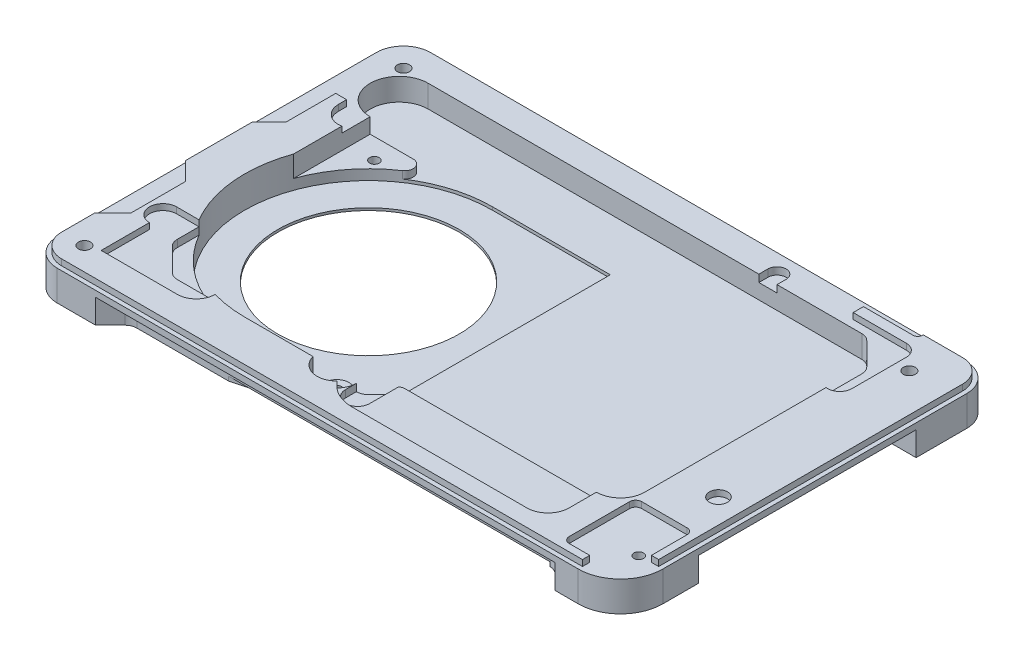
SolidWorks part; units mm, degrees
ref_plane "Front Plane" through (0, 0, 0) normal (0, 0, 1) x (1, 0, 0)
ref_plane "Top Plane" through (0, 0, 0) normal (0, 1, 0) x (1, 0, 0)
ref_plane "Right Plane" through (0, 0, 0) normal (1, 0, 0) x (0, 0, -1)
sketch "Sketch5" plane through (0, 0, 0) normal (0, 1, 0) x (1, 0, 0)
  line L1 (-44.35, -30.89) -> (41.85, -30.89)
  line L2 (-48.85, -26.39) -> (-48.85, 26.39)
  line L3 (-44.35, 30.89) -> (44.35, 30.89)
  line L4 (48.85, -23.89) -> (48.85, 26.39)
  line L5 (-48.85, -30.89) -> (48.85, 30.89) construction
  line L6 (-48.85, 30.89) -> (48.85, -30.89) construction
  arc A0 (48.85, 26.39) -> (44.35, 30.89) centre (44.35, 26.39) ccw
  arc A1 (-44.35, 30.89) -> (-48.85, 26.39) centre (-44.35, 26.39) ccw
  arc A2 (-48.85, -26.39) -> (-44.35, -30.89) centre (-44.35, -26.39) ccw
  arc A3 (41.85, -30.89) -> (48.85, -23.89) centre (41.85, -23.89) ccw
  point P0 (0, 0)
  point P18 (48.85, -22.4538)
  dimension "D3" = 4.5
  dimension "D4" = 7
  dimension "D1" = 97.7
  dimension "D2" = 61.78
extrude "Boss-Extrude2" add sketch "Sketch5" along normal blind 5
sketch "Sketch6" plane through (0, 0, 0) normal (0, -1, 0) x (1, 0, 0)
  line L0 (0, 30.89) -> (0, -30.89) construction
  line L2 (44.35, -30.89) -> (-44.35, -30.89) construction
  line L3 (-48.85, 0) -> (48.85, 0) construction
  line L4 (-48.85, -26.39) -> (-48.85, 26.39) construction
  line L6 (-47.95, 26.39) -> (-47.95, 20.2366)
  line L7 (-46.7331, 19.2604) -> (-39.7331, 20.816)
  line L8 (-38.95, 21.7922) -> (-38.95, 28.99)
  line L9 (-39.95, 29.99) -> (-44.35, 29.99)
  line L10 (39.95, 29.99) -> (41.85, 29.99)
  line L11 (38.95, 21.7922) -> (38.95, 28.99)
  line L12 (46.7331, 19.2604) -> (39.7331, 20.816)
  line L13 (47.95, 23.89) -> (47.95, 20.2366)
  line L14 (48.7658, -22.89) -> (47.95, -20.2366)
  line L15 (46.7331, -19.2604) -> (39.7331, -20.816)
  line L16 (38.95, -21.7922) -> (38.95, -28.99)
  line L17 (39.95, -29.99) -> (44.4999, -30.3558)
  line L18 (-39.95, -29.99) -> (-44.35, -29.99)
  line L19 (-38.95, -21.7922) -> (-38.95, -28.99)
  line L20 (-46.7331, -19.2604) -> (-39.7331, -20.816)
  line L21 (-47.95, -26.39) -> (-47.95, -20.2366)
  arc A0 (-47.95, 26.39) -> (-44.35, 29.99) centre (-44.35, 26.39) cw
  arc A1 (-44.35, 30.89) -> (-48.85, 26.39) centre (-44.35, 26.39) ccw construction
  arc A2 (-38.95, 21.7922) -> (-39.7331, 20.816) centre (-39.95, 21.7922) cw
  arc A3 (-39.95, 29.99) -> (-38.95, 28.99) centre (-39.95, 28.99) cw
  arc A4 (-47.95, 20.2366) -> (-46.7331, 19.2604) centre (-46.95, 20.2366) ccw
  arc A5 (47.95, 20.2366) -> (46.7331, 19.2604) centre (46.95, 20.2366) cw
  arc A6 (39.95, 29.99) -> (38.95, 28.99) centre (39.95, 28.99) ccw
  arc A7 (38.95, 21.7922) -> (39.7331, 20.816) centre (39.95, 21.7922) ccw
  arc A8 (47.95, 23.89) -> (41.85, 29.99) centre (41.85, 23.89) ccw
  arc A9 (48.7658, -22.89) -> (44.4999, -30.3558) centre (41.85, -23.89) cw
  arc A10 (38.95, -21.7922) -> (39.7331, -20.816) centre (39.95, -21.7922) cw
  arc A11 (39.95, -29.99) -> (38.95, -28.99) centre (39.95, -28.99) cw
  arc A12 (47.95, -20.2366) -> (46.7331, -19.2604) centre (46.95, -20.2366) ccw
  arc A13 (-47.95, -20.2366) -> (-46.7331, -19.2604) centre (-46.95, -20.2366) cw
  arc A14 (-39.95, -29.99) -> (-38.95, -28.99) centre (-39.95, -28.99) ccw
  arc A15 (-38.95, -21.7922) -> (-39.7331, -20.816) centre (-39.95, -21.7922) ccw
  arc A16 (-47.95, -26.39) -> (-44.35, -29.99) centre (-44.35, -26.39) ccw
  arc A17 (48.85, 23.89) -> (41.85, 30.89) centre (41.85, 23.89) ccw construction
  point P3 (0, 0)
  point P10 (0, 0)
  point P25 (-38.95, 20.99)
  point P28 (-38.95, 29.99)
  point P31 (-47.95, 18.99)
  dimension "D1" = 3.6
  dimension "D2" = 0.9
  dimension "D6" = 1
  dimension "D3" = 9
  dimension "D4" = 9
  dimension "D5" = 11
sketch "Sketch10" plane through (0, 0, 0) normal (0, -1, 0) x (1, 0, 0)
  line L0 (-48.85, 18) -> (-44.4358, 13.5858)
  line L1 (-48.85, -26.39) -> (-48.85, 26.39) construction
  line L2 (-43.85, 12.1716) -> (-43.85, -12.1716)
  line L3 (-44.4358, -13.5858) -> (-48.85, -18)
  line L4 (-48.85, -18) -> (-48.85, 18)
  line L5 (-48.85, 0) -> (48.85, 0) construction
  line L6 (48.85, 23.89) -> (48.85, -26.39) construction
  line L7 (0, 30.89) -> (0, -30.89) construction
  line L9 (44.35, -30.89) -> (-44.35, -30.89) construction
  line L10 (-38, -30.89) -> (-35.5858, -28.4758)
  line L11 (-34.1716, -27.89) -> (34.1716, -27.89)
  line L12 (35.5858, -28.4758) -> (38, -30.89)
  line L13 (-38, -30.89) -> (38, -30.89)
  line L14 (-38, 30.89) -> (38, 30.89)
  line L15 (35.5858, 28.4758) -> (38, 30.89)
  line L16 (-34.1716, 27.89) -> (34.1716, 27.89)
  line L17 (-38, 30.89) -> (-35.5858, 28.4758)
  line L21 (36.85, 18) -> (48.85, 18)
  line L22 (48.85, -18) -> (48.85, 18)
  line L23 (36.85, 15.2) -> (44.85, 15.2)
  line L24 (44.85, 15.2) -> (44.85, 14.1)
  line L25 (44.85, 14.1) -> (36.85, 14.1)
  line L27 (36.85, 11.9444) -> (44.85, 11.9444)
  line L28 (44.85, 11.9444) -> (44.85, 10.8444)
  line L29 (44.85, 10.8444) -> (36.85, 10.8444)
  line L30 (36.85, 8.6889) -> (44.85, 8.6889)
  line L31 (44.85, 8.6889) -> (44.85, 7.5889)
  line L32 (44.85, 7.5889) -> (36.85, 7.5889)
  line L33 (36.85, 5.4333) -> (44.85, 5.4333)
  line L34 (44.85, 5.4333) -> (44.85, 4.3333)
  line L35 (44.85, 4.3333) -> (36.85, 4.3333)
  line L36 (36.85, 2.1778) -> (44.85, 2.1778)
  line L37 (44.85, 2.1778) -> (44.85, 1.0778)
  line L38 (44.85, 1.0778) -> (36.85, 1.0778)
  line L41 (36.85, -1.0778) -> (44.85, -1.0778) [skipped]
  line L42 (44.85, -1.0778) -> (44.85, -2.1778) [skipped]
  line L43 (44.85, -1.0778) -> (36.85, -1.0778)
  line L44 (44.85, -2.1778) -> (44.85, -1.0778)
  line L45 (36.85, -2.1778) -> (44.85, -2.1778)
  line L46 (44.85, -4.3333) -> (36.85, -4.3333)
  line L47 (44.85, -5.4333) -> (44.85, -4.3333)
  line L48 (36.85, -5.4333) -> (44.85, -5.4333)
  line L49 (44.85, -7.5889) -> (36.85, -7.5889)
  line L50 (44.85, -8.6889) -> (44.85, -7.5889)
  line L51 (36.85, -8.6889) -> (44.85, -8.6889)
  line L52 (44.85, -10.8444) -> (36.85, -10.8444)
  line L53 (44.85, -11.9444) -> (44.85, -10.8444)
  line L54 (36.85, -11.9444) -> (44.85, -11.9444)
  line L55 (44.85, -14.1) -> (36.85, -14.1)
  line L56 (44.85, -15.2) -> (44.85, -14.1)
  line L57 (36.85, -15.2) -> (44.85, -15.2)
  line L59 (36.85, -18) -> (48.85, -18)
  arc A0 (-43.85, -12.1716) -> (-44.4358, -13.5858) centre (-45.85, -12.1716) cw
  arc A1 (-44.4358, 13.5858) -> (-43.85, 12.1716) centre (-45.85, 12.1716) cw
  arc A2 (35.5858, -28.4758) -> (34.1716, -27.89) centre (34.1716, -29.89) ccw
  arc A3 (-34.1716, -27.89) -> (-35.5858, -28.4758) centre (-34.1716, -29.89) ccw
  arc A4 (-34.1716, 27.89) -> (-35.5858, 28.4758) centre (-34.1716, 29.89) cw
  arc A5 (35.5858, 28.4758) -> (34.1716, 27.89) centre (34.1716, 29.89) cw
  arc A6 (36.85, 14.1) -> (36.85, 11.9444) centre (36.85, 13.0222) ccw
  arc A7 (36.85, 18) -> (36.85, 15.2) centre (36.85, 16.6) ccw
  arc A8 (36.85, 10.8444) -> (36.85, 8.6889) centre (36.85, 9.7667) ccw
  arc A9 (36.85, 7.5889) -> (36.85, 5.4333) centre (36.85, 6.5111) ccw
  arc A10 (36.85, 4.3333) -> (36.85, 2.1778) centre (36.85, 3.2556) ccw
  arc A11 (36.85, 1.0778) -> (36.85, -1.0778) centre (36.85, 0) ccw
  arc A12 (36.85, -4.3333) -> (36.85, -2.1778) centre (36.85, -3.2556) cw
  arc A13 (36.85, -7.5889) -> (36.85, -5.4333) centre (36.85, -6.5111) cw
  arc A14 (36.85, -10.8444) -> (36.85, -8.6889) centre (36.85, -9.7667) cw
  arc A15 (36.85, -18) -> (36.85, -15.2) centre (36.85, -16.6) cw
  arc A16 (36.85, -14.1) -> (36.85, -11.9444) centre (36.85, -13.0222) cw
  dimension "D4" = 2
  dimension "D8" = 2
  dimension "D15" = 36
  dimension "D1" = 5
  dimension "D2" = 135
  dimension "D3" = 36
  dimension "D5" = 76
  dimension "D6" = 135
  dimension "D7" = 3
  dimension "D9" = 5
  dimension "D10" = 8
  dimension "D11" = 1.1
  dimension "D12" = 12
  dimension "D13" = 8
  dimension "D14" = 2.8
extrude "Cut-Extrude2" cut sketch "Sketch10" against normal blind 4
sketch "Sketch11" plane through (0, 4, 0) normal (0, -1, 0) x (1, 0, 0)
  line L0 (-35.5858, -28.4758) -> (-38, -30.89) construction
  line L1 (-38, 30.89) -> (-35.5858, 28.4758) construction
  line L2 (-34.1716, 27.89) -> (34.1716, 27.89) construction
  line L3 (35.5858, 28.4758) -> (38, 30.89) construction
  line L4 (38, -30.89) -> (35.5858, -28.4758) construction
  line L5 (34.1716, -27.89) -> (-34.1716, -27.89) construction
  line L6 (-35.5858, -28.4758) -> (-36.5, -29.39)
  line L7 (-36.5, 29.39) -> (-35.5858, 28.4758)
  line L8 (-34.1716, 27.89) -> (34.1716, 27.89)
  line L9 (35.5858, 28.4758) -> (36.5, 29.39)
  line L10 (36.5, -29.39) -> (35.5858, -28.4758)
  line L11 (34.1716, -27.89) -> (-34.1716, -27.89)
  line L12 (-36.5, -29.39) -> (36.5, -29.39)
  line L13 (-36.5, 29.39) -> (36.5, 29.39)
  line L14 (0, -27.89) -> (0, -29.39) construction
  line L15 (0, 29.39) -> (0, 27.89) construction
  arc A0 (-34.1716, -27.89) -> (-35.5858, -28.4758) centre (-34.1716, -29.89) ccw construction
  arc A1 (34.1716, 27.89) -> (35.5858, 28.4758) centre (34.1716, 29.89) ccw construction
  arc A2 (-35.5858, 28.4758) -> (-34.1716, 27.89) centre (-34.1716, 29.89) ccw construction
  arc A3 (35.5858, -28.4758) -> (34.1716, -27.89) centre (34.1716, -29.89) ccw construction
  arc A4 (-34.1716, -27.89) -> (-35.5858, -28.4758) centre (-34.1716, -29.89) ccw
  arc A5 (34.1716, 27.89) -> (35.5858, 28.4758) centre (34.1716, 29.89) ccw
  arc A6 (-35.5858, 28.4758) -> (-34.1716, 27.89) centre (-34.1716, 29.89) ccw
  arc A7 (35.5858, -28.4758) -> (34.1716, -27.89) centre (34.1716, -29.89) ccw
  dimension "D1" = 1.5
extrude "Boss-Extrude4" add sketch "Sketch11" along normal blind 1.2
sketch "Sketch12" plane through (0, 0, -15.2) normal (0, 0, -1) x (-1, 0, 0)
  line L1 (-44.85, 4) -> (-36.85, 0)
  line L6 (-44.85, 0) -> (-36.85, 0)
  line L12 (-36.85, 0) -> (-36.85, 4)
  line L13 (-36.85, 4) -> (-44.85, 4)
  line L14 (-44.85, 4) -> (-44.85, 0)
  line L15 (-44.85, 0) -> (-36.85, 0)
  line L16 (-36.85, 0) -> (-36.85, 4) construction
  line L17 (-36.85, 4) -> (-44.85, 4) construction
  line L18 (-44.85, 4) -> (-44.85, 0)
  dimension "D1" = 0
extrude "Cut-Extrude4" cut sketch "Sketch12" against normal up to surface (30.4 mm away) up to face at (40.85, 2, 15.2)
extrude "Cut-Extrude5" cut sketch "Sketch6" against normal blind 1
sketch "Sketch13" plane through (0, 1, 0) normal (0, -1, 0) x (1, 0, 0)
  line L0 (41.85, 29.99) -> (39.95, 29.99) construction
  line L1 (38.95, 28.99) -> (38.95, 21.7922) construction
  circle A0 centre (-44.35, 26.39) radius 1
  circle A1 centre (-44.35, -26.39) radius 1
  circle A2 centre (41.85, -23.89) radius 1
  circle A4 centre (44.95, 23.99) radius 0.8
  dimension "D1" = 2
  dimension "D2" = 6
  dimension "D4" = 1.6
  dimension "D3" = 6
extrude "Cut-Extrude6" cut sketch "Sketch13" against normal through all
sketch "Sketch14" plane through (48.85, 0, 0) normal (1, 0, 0) x (0, 0, -1)
  line L1 (18, 0) -> (18, 4) construction
  line L2 (15.2, 4) -> (18, 4) construction
  line L3 (15.2, 4) -> (15.2, 0) construction
  line L5 (-15.2, 0) -> (-15.2, 4) construction
  line L6 (-18, 4) -> (-15.2, 4) construction
  line L7 (-18, 4) -> (-18, 0) construction
  line L9 (14.1, 0) -> (14.1, 4) construction
  line L10 (11.9444, 4) -> (14.1, 4) construction
  line L11 (11.9444, 4) -> (11.9444, 0) construction
  line L13 (10.8444, 0) -> (10.8444, 4) construction
  line L14 (8.6889, 4) -> (10.8444, 4) construction
  line L15 (8.6889, 4) -> (8.6889, 0) construction
  line L17 (7.5889, 0) -> (7.5889, 4) construction
  line L18 (5.4333, 4) -> (7.5889, 4) construction
  line L19 (5.4333, 4) -> (5.4333, 0) construction
  line L21 (4.3333, 0) -> (4.3333, 4) construction
  line L22 (2.1778, 4) -> (4.3333, 4) construction
  line L23 (2.1778, 4) -> (2.1778, 0) construction
  line L25 (1.0778, 0) -> (1.0778, 4) construction
  line L26 (-1.0778, 4) -> (1.0778, 4) construction
  line L27 (-1.0778, 4) -> (-1.0778, 0) construction
  line L29 (-2.1778, 0) -> (-2.1778, 4) construction
  line L30 (-4.3333, 4) -> (-2.1778, 4) construction
  line L31 (-4.3333, 4) -> (-4.3333, 0) construction
  line L33 (-5.4333, 0) -> (-5.4333, 4) construction
  line L34 (-7.5889, 4) -> (-5.4333, 4) construction
  line L35 (-7.5889, 4) -> (-7.5889, 0) construction
  line L37 (-8.6889, 0) -> (-8.6889, 4) construction
  line L38 (-10.8444, 4) -> (-8.6889, 4) construction
  line L39 (-10.8444, 4) -> (-10.8444, 0) construction
  line L41 (-11.9444, 0) -> (-11.9444, 4) construction
  line L42 (-14.1, 4) -> (-11.9444, 4) construction
  line L43 (-14.1, 4) -> (-14.1, 0) construction
  line L45 (18, 0.6) -> (18, 4)
  line L46 (15.2, 4) -> (18, 4)
  line L47 (15.2, 4) -> (15.2, 0.6)
  line L49 (-15.2, 0.6) -> (-15.2, 4)
  line L50 (-18, 4) -> (-15.2, 4)
  line L51 (-18, 4) -> (-18, 0.6)
  line L53 (14.1, 0.6) -> (14.1, 4)
  line L54 (11.9444, 4) -> (14.1, 4)
  line L55 (11.9444, 4) -> (11.9444, 0.6)
  line L57 (10.8444, 0.6) -> (10.8444, 4)
  line L58 (8.6889, 4) -> (10.8444, 4)
  line L59 (8.6889, 4) -> (8.6889, 0.6)
  line L61 (7.5889, 0.6) -> (7.5889, 4)
  line L62 (5.4333, 4) -> (7.5889, 4)
  line L63 (5.4333, 4) -> (5.4333, 0.6)
  line L65 (4.3333, 0.6) -> (4.3333, 4)
  line L66 (2.1778, 4) -> (4.3333, 4)
  line L67 (2.1778, 4) -> (2.1778, 0.6)
  line L69 (1.0778, 0.6) -> (1.0778, 4)
  line L70 (-1.0778, 4) -> (1.0778, 4)
  line L71 (-1.0778, 4) -> (-1.0778, 0.6)
  line L73 (-2.1778, 0.6) -> (-2.1778, 4)
  line L74 (-4.3333, 4) -> (-2.1778, 4)
  line L75 (-4.3333, 4) -> (-4.3333, 0.6)
  line L77 (-5.4333, 0.6) -> (-5.4333, 4)
  line L78 (-7.5889, 4) -> (-5.4333, 4)
  line L79 (-7.5889, 4) -> (-7.5889, 0.6)
  line L81 (-8.6889, 0.6) -> (-8.6889, 4)
  line L82 (-10.8444, 4) -> (-8.6889, 4)
  line L83 (-10.8444, 4) -> (-10.8444, 0.6)
  line L85 (-11.9444, 0.6) -> (-11.9444, 4)
  line L86 (-14.1, 4) -> (-11.9444, 4)
  line L87 (-14.1, 4) -> (-14.1, 0.6)
  line L88 (-18, 0.6) -> (-15.2, 0.6)
  line L89 (-18, 0) -> (-15.2, 0) construction
  line L90 (-14.1, 0.6) -> (-11.9444, 0.6)
  line L91 (-10.8444, 0.6) -> (-8.6889, 0.6)
  line L92 (-7.5889, 0.6) -> (-5.4333, 0.6)
  line L93 (-4.3333, 0.6) -> (-2.1778, 0.6)
  line L94 (-1.0778, 0.6) -> (1.0778, 0.6)
  line L95 (2.1778, 0.6) -> (4.3333, 0.6)
  line L96 (5.4333, 0.6) -> (7.5889, 0.6)
  line L97 (8.6889, 0.6) -> (10.8444, 0.6)
  line L98 (11.9444, 0.6) -> (14.1, 0.6)
  line L99 (15.2, 0.6) -> (18, 0.6)
  dimension "D1" = 0.6
sketch "Sketch15" plane through (0, 0, 0) normal (0, -1, 0) x (1, 0, 0)
  line L0 (-19, 27.89) -> (22.5938, 16.89)
  line L1 (24.5193, 17.4093) -> (35, 27.89)
  line L2 (-34.1716, 27.89) -> (34.1716, 27.89) construction
  line L3 (-48.85, 0) -> (48.85, 0) construction
  line L4 (-48.85, 18) -> (-48.85, -18) construction
  line L5 (48.85, -18) -> (48.85, 18) construction
  line L6 (35, 27.89) -> (-19, 27.89)
  line L7 (35, -27.89) -> (-19, -27.89)
  line L8 (24.5193, -17.4093) -> (35, -27.89)
  line L9 (-19, -27.89) -> (22.5938, -16.89)
  line L10 (38, -30.89) -> (35.5858, -28.4758) construction
  arc A0 (22.5938, -16.89) -> (24.5193, -17.4093) centre (23.1051, -18.8235) cw
  arc A1 (24.5193, 17.4093) -> (22.5938, 16.89) centre (23.1051, 18.8235) cw
  point P20 (23.7059, -16.5959)
  point P23 (23.7059, 16.5959)
  dimension "D3" = 2
  dimension "D1" = 54
  dimension "D2" = 11
extrude "Cut-Extrude8" cut sketch "Sketch15" against normal blind 0.7
sketch "Sketch16" plane through (0, 5, 0) normal (0, 1, 0) x (1, 0, 0)
  line L0 (-40.15, 26.29) -> (31.5718, 26.29)
  line L1 (32.986, 25.7042) -> (36.7642, 21.926)
  line L2 (37.35, 20.5118) -> (37.35, -15.39)
  line L3 (33.35, -19.39) -> (1.8069, -19.39)
  line L4 (0.3926, -19.9758) -> (-1.6858, -22.0542)
  line L7 (-34.186, -22.0042) -> (-37.9642, -18.226)
  line L8 (-38.55, -16.8118) -> (-38.55, -13.2321)
  line L9 (-40.15, 4.0209) -> (-40.15, 16.69)
  line L10 (44.35, 30.89) -> (-44.35, 30.89) construction
  line L11 (-48.85, 26.39) -> (-48.85, -26.39) construction
  line L12 (48.85, -23.89) -> (48.85, 26.39) construction
  line L13 (-44.35, -30.89) -> (41.85, -30.89) construction
  line L14 (-32.7718, -22.59) -> (-26.521, -22.59)
  line L15 (-9.5123, -23.39) -> (-20.85, -23.39)
  line L16 (-3.1, -22.64) -> (-9.5123, -22.64) construction
  arc A0 (-9.5123, -23.39) -> (-3.1, -22.64) centre (-6.35, -22.64) ccw
  arc A2 (-40.15, 26.29) -> (-40.15, 16.69) centre (-40.15, 21.49) ccw
  arc A3 (-40.15, 4.0209) -> (-38.55, -13.2321) centre (-20.85, -2.89) ccw
  circle A4 centre (-20.85, -2.89) radius 20.5 construction
  arc A5 (-26.521, -22.59) -> (-20.85, -23.39) centre (-20.85, -2.89) ccw
  arc A6 (37.35, -15.39) -> (33.35, -19.39) centre (33.35, -15.39) cw
  arc A7 (0.3926, -19.9758) -> (1.8069, -19.39) centre (1.8069, -21.39) cw
  arc A8 (-1.6858, -22.0542) -> (-3.1, -22.64) centre (-3.1, -20.64) cw
  arc A9 (-37.9642, -18.226) -> (-38.55, -16.8118) centre (-36.55, -16.8118) cw
  arc A10 (-34.186, -22.0042) -> (-32.7718, -22.59) centre (-32.7718, -20.59) ccw
  arc A11 (32.986, 25.7042) -> (31.5718, 26.29) centre (31.5718, 24.29) ccw
  arc A12 (36.7642, 21.926) -> (37.35, 20.5118) centre (35.35, 20.5118) cw
  point P26 (0, 0)
  point P27 (0, 0)
  point P31 (-6.35, -25.89)
  point P39 (1.2405, -22.64)
  point P45 (-33.6003, -22.59)
  point P48 (32.4003, 26.29)
  point P51 (37.35, 21.3403)
  dimension "D1" = 9.6
  dimension "D3" = 8.7
  dimension "D8" = 0.75
  dimension "D9" = 3.25
  dimension "D10" = 20.5
  dimension "D13" = 28
  dimension "D19" = 4
  dimension "D20" = 2
  dimension "D21" = 2
  dimension "D22" = 3.25
  dimension "D2" = 4.6
  dimension "D4" = 11.5
  dimension "D5" = 135
  dimension "D6" = 7
  dimension "D7" = 11.5
  dimension "D11" = 7.5
  dimension "D12" = 10.3
  dimension "D15" = 5
  dimension "D16" = 42.5
  dimension "D17" = 7.0793
  dimension "D18" = 8.3
extrude "Cut-Extrude10" cut sketch "Sketch16" against normal blind 3.7
sketch "Sketch17" plane through (0, 5, 0) normal (0, 1, 0) x (1, 0, 0)
  line L0 (-48.15, -20.89) -> (-48.15, -26.39)
  line L1 (-48.85, 26.39) -> (-48.85, -26.39) construction
  line L2 (-44.35, -30.89) -> (41.85, -30.89) construction
  line L3 (37.85, 30.19) -> (37.85, 30.09)
  line L4 (-48.15, 5.19) -> (-45.35, 7.99)
  line L5 (-45.35, 7.99) -> (-45.35, 16.19)
  line L6 (-45.35, 16.19) -> (-43.55, 16.19)
  line L7 (-43.55, 16.19) -> (-43.55, 14.8466)
  line L8 (-44.35, -30.19) -> (41.85, -30.19)
  line L9 (48.15, -23.89) -> (48.15, 26.39)
  line L10 (44.35, 30.19) -> (-44.35, 30.19)
  line L11 (-48.15, 26.39) -> (-48.15, -26.39)
  line L12 (-44.35, -30.19) -> (41.85, -30.19)
  line L13 (48.15, -23.89) -> (48.15, 26.39)
  line L14 (44.35, 30.19) -> (37.85, 30.19)
  line L15 (-48.15, 5.19) -> (-48.15, -5.89)
  line L16 (-42.25, -17.7321) -> (-42.25, -25.7154)
  line L17 (-40.15, 16.69) -> (-40.15, 4.0209) construction
  line L18 (-40.15, 16.69) -> (-40.15, 4.0209)
  line L19 (-20.85, -23.39) -> (-9.5123, -23.39) construction
  line L20 (-20.85, -23.39) -> (-9.5123, -23.39)
  line L21 (37.35, -15.39) -> (37.35, 20.5118) construction
  line L22 (37.35, -15.39) -> (37.35, 14.59)
  line L23 (-48.15, -5.89) -> (-45.15, -8.89)
  line L24 (-45.15, -8.89) -> (-45.15, -17.89)
  line L25 (-45.15, -17.89) -> (-48.15, -20.89)
  line L26 (-38.55, -13.2321) -> (-42.25, -13.2321)
  line L27 (-42.25, -25.7154) -> (-29.6464, -25.7154)
  line L28 (-32.7718, -22.59) -> (-26.521, -22.59) construction
  line L29 (37.05, 29.29) -> (28.85, 29.29)
  line L30 (28.85, 29.29) -> (28.85, 27.59)
  line L31 (28.85, 27.59) -> (37.65, 27.59)
  line L32 (39.65, 25.59) -> (39.65, 16.59)
  line L33 (37.65, 14.59) -> (37.35, 14.59)
  line L34 (-4.0519, -24.9381) -> (-3.3574, -25.6326)
  line L35 (0.8853, -27.39) -> (29.85, -27.39)
  line L36 (33.35, -23.89) -> (33.35, -19.39)
  line L37 (41.85, -28.99) -> (41.85, -30.19)
  line L38 (38.45, -28.99) -> (41.85, -28.99)
  line L39 (37.45, -27.99) -> (37.45, -17.99)
  line L40 (38.45, -16.99) -> (45.95, -16.99)
  line L41 (46.95, -23.89) -> (46.95, -17.99)
  line L42 (46.95, -23.89) -> (48.15, -23.89)
  line L44 (44.35, 30.89) -> (-44.35, 30.89) construction
  line L45 (48.85, -23.89) -> (48.85, 26.39) construction
  arc A0 (-9.5123, -23.39) -> (-3.1, -22.64) centre (-6.35, -22.64) ccw construction
  arc A1 (-9.5123, -23.39) -> (-4.0519, -24.9381) centre (-6.35, -22.64) ccw
  arc A2 (37.45, -27.99) -> (38.45, -28.99) centre (38.45, -27.99) ccw
  arc A3 (45.95, -16.99) -> (46.95, -17.99) centre (45.95, -17.99) cw
  arc A4 (-40.15, 4.0209) -> (-38.55, -13.2321) centre (-20.85, -2.89) ccw construction
  arc A5 (-40.15, 4.0209) -> (-38.55, -13.2321) centre (-20.85, -2.89) ccw
  arc A6 (-26.521, -22.59) -> (-20.85, -23.39) centre (-20.85, -2.89) ccw construction
  arc A7 (-26.521, -22.59) -> (-20.85, -23.39) centre (-20.85, -2.89) ccw
  arc A8 (-48.15, -26.39) -> (-44.35, -30.19) centre (-44.35, -26.39) ccw
  arc A9 (41.85, -30.19) -> (48.15, -23.89) centre (41.85, -23.89) ccw
  arc A10 (48.15, 26.39) -> (44.35, 30.19) centre (44.35, 26.39) ccw
  arc A11 (-44.35, 30.19) -> (-48.15, 26.39) centre (-44.35, 26.39) ccw
  arc A12 (-48.15, -26.39) -> (-44.35, -30.19) centre (-44.35, -26.39) ccw
  arc A13 (41.85, -30.19) -> (48.15, -23.89) centre (41.85, -23.89) ccw
  arc A14 (48.15, 26.39) -> (44.35, 30.19) centre (44.35, 26.39) ccw
  arc A16 (33.35, -19.39) -> (37.35, -15.39) centre (33.35, -15.39) ccw construction
  arc A17 (33.35, -19.39) -> (37.35, -15.39) centre (33.35, -15.39) ccw
  arc A18 (-43.55, 14.8466) -> (-40.15, 11.99) centre (-40.65, 14.8466) ccw
  arc A19 (-42.25, -13.2321) -> (-42.25, -17.7321) centre (-42.25, -15.4821) ccw
  arc A20 (-29.6464, -25.7154) -> (-26.521, -22.59) centre (-29.6464, -22.59) ccw
  arc A21 (38.45, -16.99) -> (37.45, -17.99) centre (38.45, -17.99) ccw
  circle A23 centre (44.15, -9.99) radius 1.5
  arc A24 (37.65, 27.59) -> (39.65, 25.59) centre (37.65, 25.59) cw
  arc A25 (39.65, 16.59) -> (37.65, 14.59) centre (37.65, 16.59) cw
  arc A26 (37.85, 30.09) -> (37.05, 29.29) centre (37.05, 30.09) cw
  arc A27 (29.85, -27.39) -> (33.35, -23.89) centre (29.85, -23.89) ccw
  arc A28 (0.8853, -27.39) -> (-3.3574, -25.6326) centre (0.8853, -21.39) cw
  point P48 (-44.5, -15.4821)
  point P80 (39.65, 27.59)
  point P83 (39.65, 14.59)
  point P86 (37.85, 29.29)
  line M38 (37.35, 20.5118) -> (37.35, -15.39)
  arc M39 (37.35, -15.39) -> (33.35, -19.39) centre (33.35, -15.39) cw
  arc M45 (-3.1, -22.64) -> (-9.5123, -23.39) centre (-6.35, -22.64) cw
  line M46 (-9.5123, -23.39) -> (-20.85, -23.39)
  arc M47 (-20.85, -23.39) -> (-26.521, -22.59) centre (-20.85, -2.89) cw
  arc M53 (-38.55, -13.2321) -> (-40.15, 4.0209) centre (-20.85, -2.89) cw
  line M54 (-40.15, 4.0209) -> (-40.15, 16.69)
  dimension "D2" = 135
  dimension "D5" = 4.5
  dimension "D11" = 0.5
  dimension "D13" = 4.7
  dimension "D16" = 1
  dimension "D17" = 2.8
  dimension "D22" = 3
  dimension "D31" = 2
  dimension "D32" = 0.8
  dimension "D33" = 3.5
  dimension "D34" = 6
  dimension "D3" = 135
  dimension "D4" = 3.7
  dimension "D6" = 15
  dimension "D7" = 6.6
  dimension "D8" = 10
  dimension "D9" = 1.8
  dimension "D10" = 3.5
  dimension "D12" = 0.5
  dimension "D14" = 11
  dimension "D15" = 14
  dimension "D18" = 135
  dimension "D19" = 12
  dimension "D20" = 9.5
  dimension "D21" = 1.2
  dimension "D23" = 4
  dimension "D24" = 7
  dimension "D25" = 1.7
  dimension "D26" = 2.3
  dimension "D27" = 1.6
  dimension "D28" = 9
  dimension "D29" = 11
  dimension "D30" = 13
  dimension "D1" = 0.7
extrude "Boss-Extrude5" add sketch "Sketch17" along normal blind 1 contours L35 A28 L34 A20 L27 L16 A19 L26 A18 L7 L6 L5 L4 L15 L23 L24 L25 L0 A12 L12 L37 L38 A2 L39 A21 L40 A3 L41 L42 L13 A14 L14 L3 A26 L29 L30 L31 A24 L32 A25 L33 L36 A27 M45 M46 M47 M53 M54 M38 M39
sketch "Sketch18" plane through (0, 5, 0) normal (0, 1, 0) x (1, 0, 0)
  line L0 (-3.1, -22.64) -> (-3.1, -24.44)
  line L1 (0.9, -19.6074) -> (0.9, -24.44)
  line L2 (-1.6858, -22.0542) -> (0.3926, -19.9758) construction
  line L7 (14.55, 26.29) -> (14.55, 27.79)
  line L8 (31.5718, 26.29) -> (-40.15, 26.29) construction
  line L9 (17.55, 26.29) -> (17.55, 27.79)
  line L10 (14.55, 26.29) -> (17.55, 26.29)
  line L11 (48.85, -23.89) -> (48.85, 26.39) construction
  line L12 (-1.6858, -22.0542) -> (0.3926, -19.9758)
  arc A0 (-3.1, -24.44) -> (0.9, -24.44) centre (-1.1, -24.44) ccw
  arc A3 (14.55, 27.79) -> (17.55, 27.79) centre (16.05, 27.79) cw
  arc A4 (-3.1, -22.64) -> (-1.6858, -22.0542) centre (-3.1, -20.64) ccw construction
  arc A5 (-3.1, -22.64) -> (-1.6858, -22.0542) centre (-3.1, -20.64) ccw
  arc A6 (1.8069, -19.39) -> (0.3926, -19.9758) centre (1.8069, -21.39) ccw construction
  arc A7 (1.8069, -19.39) -> (0.3926, -19.9758) centre (1.8069, -21.39) ccw construction
  arc A8 (0.9, -19.6074) -> (0.3926, -19.9758) centre (1.8069, -21.39) ccw
  point P6 (0, 0)
  point P12 (0, 0)
  point P13 (0, 0)
  dimension "D1" = 2
  dimension "D4" = 2
  dimension "D5" = 1.5
  dimension "D6" = 31.3
  dimension "D2" = 1.8
  dimension "D7" = 1.5
extrude "Cut-Extrude11" cut sketch "Sketch18" against normal blind 1.2
sketch "Sketch19" plane through (0, 0, 0) normal (0, -1, 0) x (1, 0, 0)
  circle A0 centre (-20.85, 2.89) radius 20
  arc A3 (-38.55, 13.2321) -> (-40.15, -4.0209) centre (-20.85, 2.89) ccw construction
  point P2 (-40.85, 2.89)
  point P3 (-20.85, 22.89)
  dimension "D1" = 40
extrude "Cut-Extrude12" cut sketch "Sketch19" against normal blind 0.4
sketch "Sketch20" plane through (0, 0.4, 0) normal (0, -1, 0) x (1, 0, 0)
  circle A1 centre (-20.85, 2.89) radius 15
  circle A2 centre (-20.85, 2.89) radius 20
  circle A3 centre (-20.85, 2.89) radius 20 construction
  dimension "D2" = 30
  dimension "D1" = 0
extrude "Cut-Extrude13" cut sketch "Sketch20" against normal through all
sketch "Sketch21" plane through (0, 1.3, 0) normal (0, 1, 0) x (1, 0, 0)
  line L0 (-20.85, 17.61) -> (-1.35, 17.61)
  line L1 (-1.35, 17.61) -> (-1.35, -21.7184)
  line L2 (-1.6858, -22.0542) -> (0.3926, -19.9758) construction
  line L3 (-20.85, -23.39) -> (-9.5123, -23.39) construction
  line L4 (-1.6858, -22.0542) -> (-1.35, -21.7184)
  line L5 (-20.85, -23.39) -> (-9.5123, -23.39)
  arc A3 (-3.1, -22.64) -> (-1.6858, -22.0542) centre (-3.1, -20.64) ccw construction
  arc A6 (-20.85, 17.61) -> (-20.85, -23.39) centre (-20.85, -2.89) ccw
  arc A7 (-9.5123, -23.39) -> (-3.1, -22.64) centre (-6.35, -22.64) ccw construction
  arc A8 (-3.1, -22.64) -> (-1.6858, -22.0542) centre (-3.1, -20.64) ccw
  arc A9 (-9.5123, -23.39) -> (-3.1, -22.64) centre (-6.35, -22.64) ccw
  point P1 (0, 0)
  point P7 (0, 0)
  point P11 (-41.35, -2.89)
  point P14 (0, 0)
  point P15 (-1.6858, -19.5171)
  point P16 (-0.6466, -21.015)
  point P17 (0, 0)
  point P18 (0, 0)
  point P19 (0.949, -19.4195)
  dimension "D1" = 40
  dimension "D2" = 0
extrude "Cut-Extrude14" cut sketch "Sketch21" against normal blind 0.5
sketch "Sketch23" plane through (0, 1.3, 0) normal (0, 1, 0) x (1, 0, 0)
  line L0 (-40.15, 16.69) -> (-40.15, 4.0209) construction
  line L1 (-40.15, 16.69) -> (-40.15, 4.0209)
  line L2 (-40.15, 16.69) -> (-33.0454, 16.69)
  line L4 (-3.1, -22.64) -> (-3.5216, -22.64)
  line L5 (-48.85, 26.39) -> (-48.85, -26.39) construction
  line L6 (44.35, 30.89) -> (-44.35, 30.89) construction
  arc A0 (-9.5123, -23.39) -> (-3.1, -22.64) centre (-6.35, -22.64) ccw construction
  arc A1 (-3.5216, -22.64) -> (-4.4644, -21.9733) centre (-3.5216, -21.64) cw
  arc A2 (-20.85, 17.61) -> (-20.85, -23.39) centre (-20.85, -2.89) ccw construction
  arc A3 (-9.5123, -23.39) -> (-3.1, -22.64) centre (-6.35, -22.64) ccw
  arc A4 (-8.3438, -22.4832) -> (-4.4644, -21.9733) centre (-6.35, -22.64) cw
  arc A5 (-32.2682, 14.1357) -> (-40.15, 4.0209) centre (-20.85, -2.89) ccw
  arc A6 (-32.2682, 14.1357) -> (-33.0454, 16.69) centre (-33.0454, 15.2946) ccw
  arc A8 (-8.3438, -22.4832) -> (-9.5123, -23.39) centre (-9.3408, -22.4048) cw
  circle A9 centre (-36.05, 13.29) radius 0.8
  circle A10 centre (-6.35, -22.64) radius 0.8
  point P17 (-31.65, 15.2946)
  point P20 (-36.85, 13.29)
  point P21 (-36.05, 14.09)
  point P26 (0, 0)
  dimension "D1" = 8.5
  dimension "D2" = 2
  dimension "D3" = 1
  dimension "D4" = 1.6
  dimension "D5" = 12
  dimension "D6" = 16.8
extrude "Boss-Extrude6" add sketch "Sketch23" along normal blind 1.2
sketch "Sketch24" plane through (0, 1.3, 0) normal (0, 1, 0) x (1, 0, 0)
  line L3 (-38.55, -13.2321) -> (-38.55, -16.8118)
  line L4 (-37.9642, -18.226) -> (-34.186, -22.0042)
  line L5 (-32.7718, -22.59) -> (-26.521, -22.59)
  line L6 (-38.55, -13.2321) -> (-38.55, -16.8118)
  line L7 (-37.9642, -18.226) -> (-34.186, -22.0042)
  line L8 (-32.7718, -22.59) -> (-26.521, -22.59)
  arc A3 (-38.55, -13.2321) -> (-26.521, -22.59) centre (-20.85, -2.89) ccw
  arc A4 (-38.55, -16.8118) -> (-37.9642, -18.226) centre (-36.55, -16.8118) ccw
  arc A5 (-34.186, -22.0042) -> (-32.7718, -22.59) centre (-32.7718, -20.59) ccw
  arc A6 (-38.55, -13.2321) -> (-26.521, -22.59) centre (-20.85, -2.89) ccw
  arc A7 (-38.55, -16.8118) -> (-37.9642, -18.226) centre (-36.55, -16.8118) ccw
  arc A8 (-34.186, -22.0042) -> (-32.7718, -22.59) centre (-32.7718, -20.59) ccw
  dimension "D1" = 0
extrude "Boss-Extrude7" add sketch "Sketch24" along normal offset from surface (2.5 mm away) 1.2 up to face at (-36.6741, 5, 19.8696)
